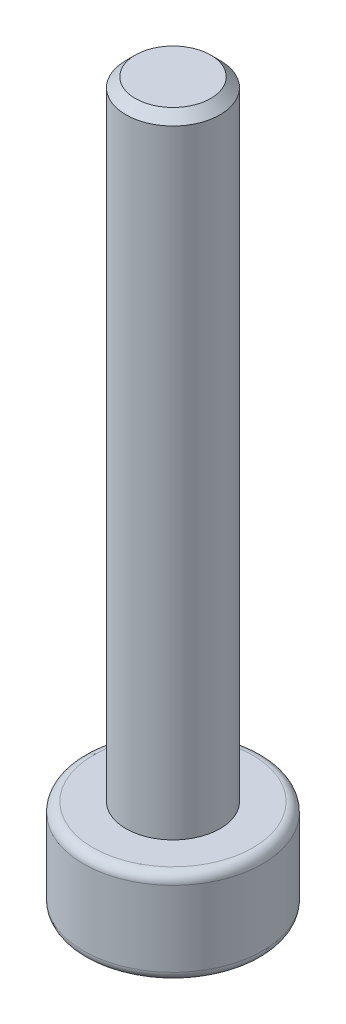
SolidWorks part; units mm, degrees
material "AISI 304"
ref_plane "前视基准面" through (0, 0, 0) normal (0, 0, 1) x (1, 0, 0)
ref_plane "上视基准面" through (0, 0, 0) normal (0, 1, 0) x (1, 0, 0)
ref_plane "右视基准面" through (0, 0, 0) normal (1, 0, 0) x (0, 0, -1)
sketch "草图1" plane through (0, 0, 0) normal (0, 1, 0) x (1, 0, 0)
  circle A0 centre (0, 0) radius 2.85
  dimension "D1" = 5.7
extrude "凸台-拉伸1" add sketch "草图1" along normal blind 3
sketch "草图2" plane through (0, 3, 0) normal (0, 1, 0) x (1, 0, 0)
  circle A0 centre (0, 0) radius 1.5
  dimension "D1" = 3
extrude "凸台-拉伸2" add sketch "草图2" along normal blind 20
sketch "草图3" plane through (0, 0, 0) normal (0, -1, 0) x (1, 0, 0)
  circle A0 centre (0, 0) radius 1.29
  dimension "D1" = 2.58
extrude "切除-拉伸1" cut sketch "草图3" against normal blind 1.3
fillet "圆角1" radius 0.3 2 edges at (0, 3, 2.85) (0, 0, 2.85)
chamfer "倒角1" distance 0.3 angle 45 1 edges at (0, 23, 1.5)
chamfer "倒角2" distance 0.15 angle 45 1 edges at (0, 0, -1.29)
